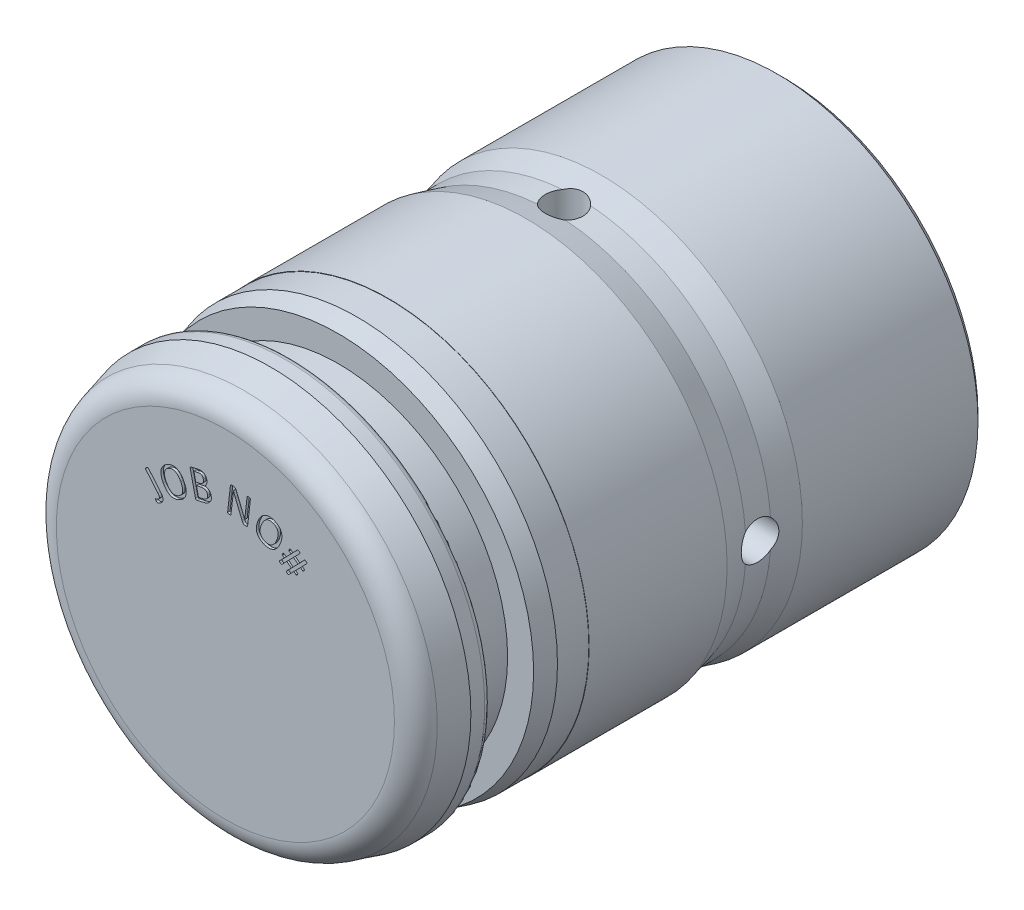
SolidWorks part; units mm, degrees
ref_plane "Front" through (0, 0, 0) normal (0, 0, 1) x (1, 0, 0)
ref_plane "Top" through (0, 0, 0) normal (0, 1, 0) x (1, 0, 0)
ref_plane "Right" through (0, 0, 0) normal (1, 0, 0) x (0, 0, -1)
sketch "Sketch1" plane through (0, 0, 0) normal (1, 0, 0) x (0, 0, -1)
  line L0 (0, 0) -> (10, 0) construction
  line L1 (34, 16) -> (36, 15.5)
  line L2 (54.5, 13.2774) -> (54.5, 15.5)
  line L3 (10, 5) -> (0, 5)
  line L4 (15.2, 13.5) -> (19, 13.5)
  line L5 (15.2, 13.5) -> (15.2, 15.475)
  line L6 (19, 13.5) -> (19, 15.5731)
  line L7 (23, 16) -> (34, 16)
  line L8 (10, 13.4766) -> (10, 5)
  line L9 (54, 16) -> (54.5, 15.5)
  line L10 (36, 15.5) -> (38, 15.5)
  line L11 (15.2, 0.1519) -> (15.2, 16.1519) construction
  line L12 (19, 0.1519) -> (19, 16.1519) construction
  line L13 (19, 15.5731) -> (20.5, 15.975)
  line L14 (0, 0) -> (16.9957, 0)
  line L15 (11.4824, 15.4085) -> (13.5967, 15.975)
  line L16 (38.0035, 13.0864) -> (39.4455, 12.7)
  line L17 (39.4455, 12.7) -> (53.5, 12.7)
  line L18 (37.5, 9.5774) -> (37.5, 12.7)
  line L19 (20, 5) -> (20, 9)
  line L20 (20.5035, 9.3864) -> (21.9455, 9)
  line L21 (37.5, 0) -> (37.5, 15.5) construction
  line L22 (0, 5) -> (0, 0)
  line L23 (36.5, 9) -> (37.5, 9.5774)
  line L24 (20, 0) -> (20, 15.5) construction
  line L25 (54.5, 0) -> (54.5, 15.5) construction
  line L26 (53.5, 12.7) -> (54.5, 13.2774)
  line L27 (21.9455, 9) -> (36.5, 9)
  line L28 (20, 5) -> (16.9957, 0)
  line L31 (10, 0) -> (0, 0) construction
  line L33 (13.5967, 15.975) -> (14.7, 15.975)
  line L34 (23, 15.975) -> (23, 16)
  line L35 (20.5, 15.975) -> (23, 15.975)
  line L36 (38, 15.5) -> (40, 16)
  line L37 (40, 16) -> (54, 16)
  arc A0 (15.2, 15.475) -> (14.7, 15.975) centre (14.7, 15.475) ccw
  arc A1 (20.5035, 9.3864) -> (20, 9) centre (20.4, 9) ccw
  arc A2 (38.0035, 13.0864) -> (37.5, 12.7) centre (37.9, 12.7) ccw
  arc A3 (10, 13.4766) -> (11.4824, 15.4085) centre (12, 13.4766) cw
  point P2 (0, 16)
  point P4 (54.5, 16)
  point P5 (0, 13.5)
  point P6 (51.287, 13.5)
  point P22 (0, 11)
  point P23 (51.287, 11)
  point P24 (0, 12.7)
  point P25 (51.287, 12.7)
  point P28 (37.5, 9)
  point P43 (54.5, 14.3887)
  dimension "D12" = 0.5
  dimension "D21" = 0.8
  dimension "D34" = 15.975
  dimension "D35" = 165
  dimension "D42" = 2
  dimension "D43" = 0.8
  dimension "D44" = 165
  dimension "D5" = 3.8
  dimension "D6" = 5
  dimension "D7" = 45
  dimension "D8" = 16
  dimension "D9" = 15
  dimension "D10" = 44.5
  dimension "D11" = 15
  dimension "D13" = 15.5
  dimension "D14" = 13.5
  dimension "D15" = 34.5
  dimension "D16" = 17
  dimension "D17" = 1
  dimension "D18" = 9
  dimension "D19" = 1.5
  dimension "D20" = 30
  dimension "D22" = 1
  dimension "D23" = 0.5
  dimension "D24" = 31.5
  dimension "D25" = 13
  dimension "D26" = 31
  dimension "D27" = 12.7
  dimension "D28" = 0.5774
  dimension "D29" = 3.7
  dimension "D30" = 150
  dimension "D31" = 14.036
  dimension "D32" = 5
  dimension "D33" = 20
  dimension "D36" = 5.2
  dimension "D37" = 14.5
  dimension "D38" = 20.5
  dimension "D39" = 16.5
  dimension "D40" = 18.5
  dimension "D41" = 3.5967
  dimension "D45" = 0
revolve "Revolve1" add sketch "Sketch1" angle 360 about L0
sketch "Sketch2" plane through (0, 0, 0) normal (1, 0, 0) x (0, 0, -1)
  line L0 (54.5, -15.5) -> (54.5, 15.5) construction
  line L1 (37, 16) -> (38.5, 16)
  line L2 (37, 16) -> (37, 8)
  line L3 (37, 8) -> (38.5, 8)
  line L4 (38.5, 16) -> (38.5, 8)
  dimension "D1" = 1.5
  dimension "D2" = 8
  dimension "D3" = 16
  dimension "D4" = 16
revolve "Cut-Revolve1" cut sketch "Sketch2" angle 360 about L2
pattern_circular "CirPattern1" count 4 over 360 about axis through (0, 0, -34) along (0, 0, 1) of "Cut-Revolve1"
hole_wizard "CSK for M2.5 Cross Countersunk Head Screw1" positions "Sketch4" profile "Sketch6" countersink size "M2.5" standard "AS"
sketch "Sketch4" plane through (0, 0, 0) normal (0, 0, 1) x (1, 0, 0)
  point P0 (0, 0)
sketch "Sketch6" plane through (0, 0, 0) normal (1, 0, 0) x (0, -1, 0)
  line L0 (0, 0) -> (0, 3)
  line L1 (0, 3) -> (1.575, 2.0536)
  line L2 (1.575, 2.0536) -> (1.575, 0.6518)
  line L3 (1.575, 0.6518) -> (2.25, 0)
  line L5 (2.25, 0) -> (0, 0)
  line L6 (-1.575, 0.6518) -> (-2.25, 0) construction
  line L10 (0, 3) -> (-1.575, 2.0536) construction
  line L11 (0, -6.35) -> (0, 107.95) construction
  dimension "Hole Dia." = 3.15
  dimension "Hole Depth" = 3
  dimension "Near C'Sink Dia." = 4.5
  dimension "Near C'Sink Angle" = 92
  dimension "Drill Angle" = 118
sketch "Sketch7" plane through (0, 0, -10) normal (0, 0, 1) x (1, 0, 0)
  circle A0 centre (0, 0) radius 13.4766
extrude "Cut-Extrude1" cut sketch "Sketch7" along normal through all
sketch "Sketch8" plane through (0, 0, -10) normal (0, 0, 1) x (1, 0, 0)
  arc A0 (6.7132, 3.9878) -> (-6.7132, 3.9878) centre (0, 0) ccw construction
  text T0 "JOB NO#" font "Calibri" height in points 8
extrude "Cut-Extrude2" cut sketch "Sketch8" against normal blind 0.2
sketch "Sketch9" [suppressed] plane through (0, 0, 0) normal (1, 0, 0) x (0, 0, -1)
  line L0 (23, 16) -> (23, -16) construction
  line L1 (23, 16) -> (23, -16) construction
  line L2 (40, 16) -> (40, -16) construction
  line L3 (40, 16) -> (40, -16) construction
  line L4 (23, 16) -> (34, 16)
  line L5 (23, 16.075) -> (33.7, 16.075)
  line L7 (23, 16.075) -> (34, 16.075) construction
  line L8 (23, 16.075) -> (23, 16)
  line L9 (40, 16) -> (54, 16)
  line L10 (40.3, 16.075) -> (53.925, 16.075)
  line L11 (54, 16) -> (53.925, 16.075)
  line L12 (40, 16.075) -> (54, 16.075) construction
  line L13 (40, 16) -> (38.4999, 15.625) construction
  line L14 (40.3, 16.075) -> (40, 16)
  line L15 (0, 0) -> (54.5, 0) construction
  line L16 (54.5, -15.5) -> (54.5, 15.5) construction
  line L17 (35.5001, 15.625) -> (34, 16) construction
  line L18 (34, 16) -> (33.7, 16.075)
  dimension "D1" = 0.075
  dimension "D3" = 0.075
  dimension "D4" = 0.075
revolve "Revolve2" [suppressed] add sketch "Sketch9" angle 360 about L15
